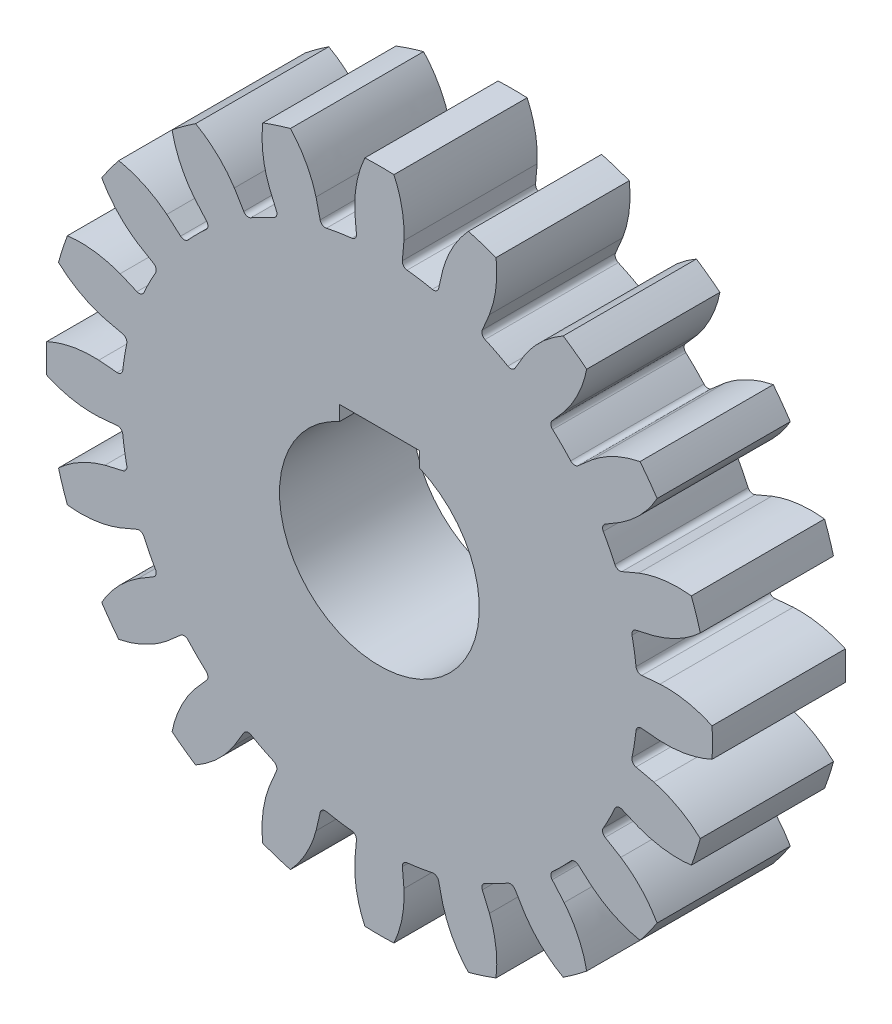
SolidWorks part; units mm, degrees
material "201 Annealed Stainless Steel (SS)"
ref_plane "Front Plane" through (0, 0, 0) normal (0, 0, 1) x (1, 0, 0)
ref_plane "Top Plane" through (0, 0, 0) normal (0, 1, 0) x (1, 0, 0)
ref_plane "Right Plane" through (0, 0, 0) normal (1, 0, 0) x (0, 0, -1)
sketch "Sketch1" plane through (0, 0, 0) normal (0, 0, 1) x (1, 0, 0)
  line L0 (-38.75, 0) -> (-50, 0) construction
  line L1 (0, 0) -> (76.4864, 0) construction
  line L2 (0, 0) -> (77.5758, 13.6787) construction
  line L3 (0, 0) -> (54.3016, 4.7508) construction
  line L4 (0, 0) -> (49.9524, 2.181) construction
  line L5 (42.1241, 3.6854) -> (38.6025, 3.3773)
  line L6 (38.1613, 6.7289) -> (0, 0)
  line L7 (42.1241, -3.6854) -> (38.6025, -3.3773)
  line L8 (38.1613, -6.7289) -> (0, 0)
  circle A0 centre (0, 0) radius 50 construction
  circle A1 centre (0, 0) radius 42.285 construction
  arc A2 (-38.75, 0) -> (38.7131, 1.6903) centre (0, 0) ccw construction
  arc A3 (38.6025, 3.3773) -> (38.1613, 6.7289) centre (0, 0) ccw
  arc A4 (38.6025, -3.3773) -> (38.1613, -6.7289) centre (0, 0) cw
  arc A5 (49.9524, 2.181) -> (49.9524, -2.181) centre (0, 0) cw
  spline S0 degree 2 poles (49.9524, 2.181) (46.2291, 3.8843) (42.1241, 3.6854) knots 0 0 0 1 1 1
  spline S1 degree 2 poles (49.9524, -2.181) (46.2291, -3.8843) (42.1241, -3.6854) knots 0 0 0 1 1 1
  dimension "D1" = 100
  dimension "D2" = 84.57
  dimension "D3" = 11.25
  dimension "D4" = 10
  dimension "D5" = 5
  dimension "D6" = 2.5
extrude "Boss-Extrude1" add sketch "Sketch1" along normal blind 20
fillet "Fillet1" radius 0.8 2 edges at (38.6025, -3.3773, 10) (38.6025, 3.3773, 10)
pattern_circular "CirPattern4" count 20 over 360 about axis through (0, 0, 20) along (0, 0, -1) of "Boss-Extrude1", "Fillet1"
sketch "Sketch2" plane through (0, 0, 20) normal (0, 0, 1) x (1, 0, 0)
  line L0 (0, 0) -> (0, 24.9342) construction
  line L1 (6, 13.7477) -> (6, 15.9977)
  line L2 (-6, 13.7477) -> (-6, 15.9977)
  line L3 (6, 0) -> (6, 24.9342) construction
  line L4 (-6, 0) -> (-6, 24.9342) construction
  line L5 (-6, 13.7477) -> (-6, 15.9977)
  line L6 (6, 13.7477) -> (6.0568, 13.7749)
  line L7 (-6, 15.9977) -> (6, 15.9977)
  line L8 (-25.2588, 0) -> (25.2588, 0) construction
  arc A0 (-6, 13.7477) -> (6, 13.7477) centre (0, 0) ccw
  point P15 (0, 0)
  dimension "D1" = 30
  dimension "D2" = 2.25
  dimension "D3" = 12
extrude "Cut-Extrude1" cut sketch "Sketch2" against normal through all
